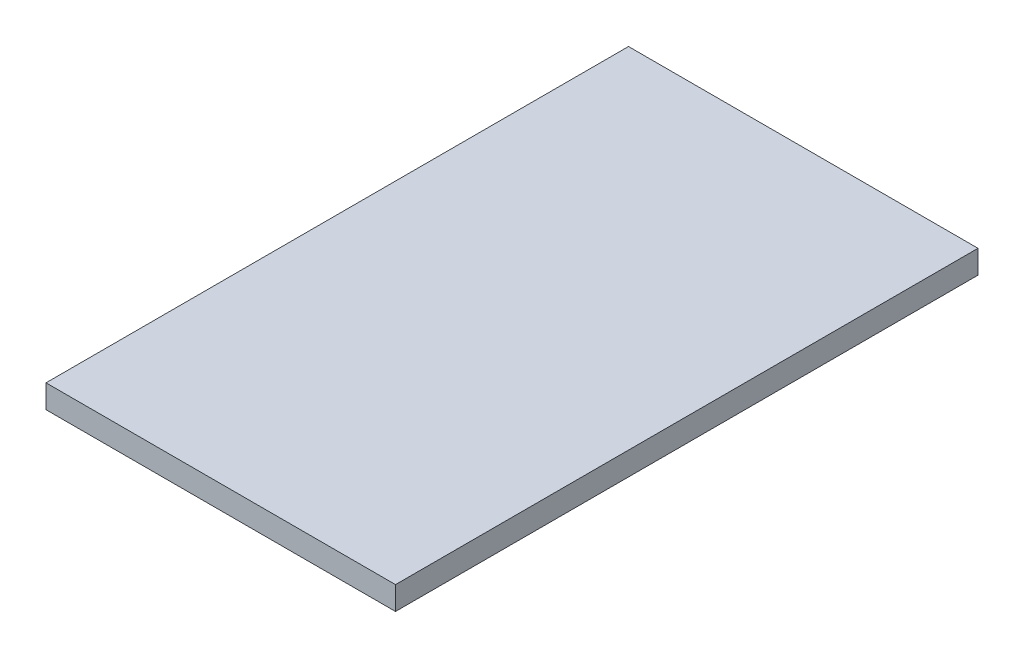
SolidWorks part; units mm, degrees
ref_plane "Front Plane" through (0, 0, 0) normal (0, 0, 1) x (1, 0, 0)
ref_plane "Top Plane" through (0, 0, 0) normal (0, 1, 0) x (1, 0, 0)
ref_plane "Right Plane" through (0, 0, 0) normal (1, 0, 0) x (0, 0, -1)
sketch "Sketch1" plane through (0, 0, 0) normal (0, 1, 0) x (1, 0, 0)
  line L1 (0, 0) -> (30, 0)
  line L2 (0, 0) -> (0, 50)
  line L3 (0, 50) -> (30, 50)
  line L4 (30, 0) -> (30, 50)
  dimension "D1" = 50
  dimension "D2" = 30
extrude "Boss-Extrude1" add sketch "Sketch1" along normal blind 2
